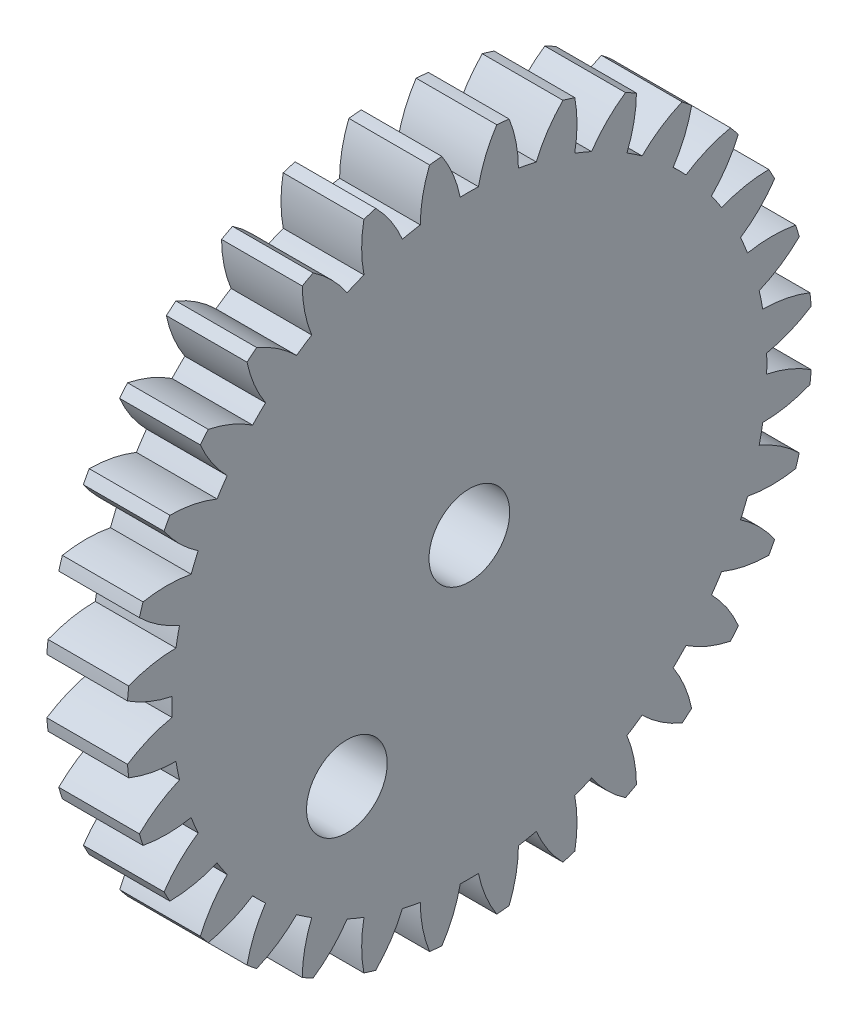
SolidWorks part; units mm, degrees
ref_plane "Plane1" through (0, 0, 0) normal (0, 0, 1) x (1, 0, 0)
ref_plane "Plane2" through (0, 0, 0) normal (0, 1, 0) x (1, 0, 0)
ref_plane "Plane3" through (0, 0, 0) normal (1, 0, 0) x (0, 0, -1)
sketch "HoldingSke" plane through (0, 0, 0) normal (0, 1, 0) x (1, 0, 0)
  line L0 (0, 0) -> (3.3922, -2.1197)
  line L1 (-15, 0) -> (100, 0) construction
  line L2 (0, 0) -> (-2.1039, 2.3779)
  line L3 (0, 0) -> (-11.863, 4.5341)
  line L4 (0, 0) -> (7.3237, 4.5764)
  line L5 (0, 0) -> (-46.8476, -17.4728)
  line L6 (0, 0) -> (-0.829, -0.5593)
  line L7 (-2.1039, 2.3779) -> (8.6586, 51.2059)
  line L8 (-76.2, 54.61) -> (-76.1, 54.61)
  line L9 (-71.009, 38.7566) -> (-53.1078, 45.2721)
  line L10 (-76.2, 71.12) -> (104.1128, 71.12)
  line L11 (0, 0) -> (-1, 0)
  line L12 (-76.2, 101.6) -> (-76.192, 101.6)
  line L13 (24.9733, 27.94) -> (52.9518, 28.4284)
  line L14 (24.9733, 27.94) -> (24.9743, 27.94)
  line L15 (24.9733, 27.94) -> (100.4006, 29.5858)
  line L16 (-63.627, -0.25) -> (-12.827, -0.25)
  circle A0 centre (0, 0) radius 0.625
  circle A1 centre (0, 0) radius 3.6865
  circle A2 centre (0, 0) radius 37.5
  circle A3 centre (0, 0) radius 0.625
  dimension "MHD" = 7.373
  dimension "Hub_dia" = 75
  dimension "Bore" = 1.25
  dimension "MBD" = 1.25
  dimension "Num_teeth" = 32
  dimension "Pitch" = 4
  dimension "Overall_len" = 50
  dimension "Show_teeth" = 32
  dimension "Thickness" = 1
  dimension "OAL" = 50.0001
  dimension "T_dim" = 0.1
  dimension "Ap" = 20
  dimension "H" = 19.05
  dimension "Pitch_radius" = 180.3128
  dimension "Width" = 1
  dimension "Backlash" = 0.008
  dimension "Addendum_fac" = 1
  dimension "Dedendum_fac" = 1.25
  dimension "Clearance_fac" = 0.25
  dimension "Dedendum_add" = 0.001
  dimension "Module" = 0.25
sketch "BasProSke" plane through (0, 0, 0) normal (0, 1, 0) x (1, 0, 0)
  line L0 (-10, 0) -> (60, 0) construction
  line L1 (0, 0) -> (0, 4.25)
  line L2 (0, 0) -> (1, 0)
  line L3 (1, 0) -> (1, 4.25)
  line L4 (1, 4.25) -> (0, 4.25)
  dimension "Thickness" = 1
  dimension "Diameter" = 8.5
revolve "Base-Revolve" add sketch "BasProSke" angle 360 about L0
sketch "TooCutSke" plane through (0, 0, 0) normal (1, 0, 0) x (0, 0, -1)
  line L1 (0, 0) -> (0, 107) construction
  line L2 (0, 0) -> (-0.2103, 3.9945) construction
  line L3 (0, 0) -> (-0.7833, 7.9532) construction
  line L4 (-0.2103, 3.9945) -> (-0.3917, 3.9766) construction
  arc A0 (0.1129, 3.6848) -> (-0.1129, 3.6848) centre (0, 0) ccw
  arc A1 (0.356, 4.2606) -> (-0.356, 4.2606) centre (0, 0) ccw
  circle A2 centre (0, 0) radius 4 construction
  circle A3 centre (0, 0) radius 3.7588 construction
  arc A4 (-0.1129, 3.6848) -> (-0.356, 4.2606) centre (-1.6801, 3.3624) ccw
  arc A5 (0.356, 4.2606) -> (0.1129, 3.6848) centre (1.6801, 3.3624) ccw
  dimension "Root_dia" = 7.373
  dimension "Overcut_dia" = 8.5508
  dimension "Pitch_dia" = 8
  dimension "Base_dia" = 7.5175
  dimension "Flank_rad" = 1.6
  dimension "Half_ang" = 5.625
  dimension "Half_CT" = 0.1823
extrude "ToothCut" cut sketch "TooCutSke" along normal through all
fillet "Breaks" [suppressed] radius 0.005
fillet "RootFillets" [suppressed] radius 0.0635
pattern_circular "TeethCuts" count 32 every 11.25 about axis through (-10, 0, 0) along (1, 0, 0) of "ToothCut", "RootFillets", "Breaks"
sketch "HubNeaOneSke" plane through (0, 0, 0) normal (-1, 0, 0) x (0, 0, 1)
  circle A0 centre (0, 0) radius 3.6865
  dimension "Diameter" = 7.373
extrude "HubNearOne" [suppressed] add sketch "HubNeaOneSke" along normal blind 49.0001
sketch "HubNeaBotSke" plane through (0, 0, 0) normal (-1, 0, 0) x (0, 0, 1)
  circle A0 centre (0, 0) radius 3.6865
  dimension "Diameter" = 7.373
extrude "HubNearBoth" [suppressed] add sketch "HubNeaBotSke" along normal blind 24.5
ref_plane "FarPln" through (1, 0, 0) normal (1, 0, 0) x (0, 0, -1)
sketch "HubFarSke" plane through (1, 0, 0) normal (1, 0, 0) x (0, 0, -1)
  circle A0 centre (0, 0) radius 3.6865
  dimension "Diameter" = 7.373
extrude "HubFar" [suppressed] add sketch "HubFarSke" along normal blind 24.5
sketch "BorSke" plane through (0, 0, 0) normal (1, 0, 0) x (0, 0, -1)
  circle A0 centre (0, 0) radius 0.5
  dimension "Diameter" = 1
extrude "Bore" cut sketch "BorSke" along normal mid plane 100.0001
sketch "KeySke" plane through (0, 0, 0) normal (1, 0, 0) x (0, 0, -1)
  line L0 (-0.05, 0) -> (-0.05, 0.725)
  line L1 (-0.05, 0.725) -> (0.05, 0.725)
  line L2 (0.05, 0.725) -> (0.05, 0)
  line L3 (0, 0) -> (0, 34) construction
  line L4 (-0.05, 0) -> (0.05, 0)
  dimension "Offset" = 0.725
extrude "Keyway" [suppressed] cut sketch "KeySke" along normal mid plane 100.0001
pattern_circular "Keyway2" [suppressed] count 2 every 90 about axis through (-10, 0, 0) along (1, 0, 0)
sketch "草圖1" plane through (1, 0, 0) normal (1, 0, 0) x (0, 0, -1)
  circle A0 centre (-1.5178, -1.9355) radius 0.5
  dimension "D1" = 1
extrude "除料-伸長1" cut sketch "草圖1" against normal blind 10
equation "' \"Module@HoldingSke\" = 6.35"
equation "' \"Num_teeth@HoldingSke\" = 12"
equation "' \"Ap@HoldingSke\" =  20"
equation "' \"Ap@HoldingSke\" = 20"
equation "' \"Width@HoldingSke\" = 0.5 * 25.4"
equation "' \"Hub_dia@HoldingSke\"= 1 * 25.4"
equation "' \"Hub_dia@HoldingSke\" = 1 * 25.4"
equation "' \"Overall_len@HoldingSke\" = 1.0 * 25.4"
equation "' \"Bore@HoldingSke\" = 0.75 * 25.4"
equation "' \"T_dim@HoldingSke\" = 0.1 * 25.4"
equation "' \"Width@KeySke\" = 0.25 * 25.4"
equation "' \"Show_teeth@HoldingSke\" = 13"
equation "' \"Backlash@HoldingSke\" = 0.009 * 25.4"
equation "' \"Addendum_fac@HoldingSke\" = 1.0"
equation "' \"Dedendum_fac@HoldingSke\" = 1.25"
equation "' \"Dedendum_add@HoldingSke\" = 0.00005 * 25.4"
equation "' \"Clearance_fac@HoldingSke\" = 0.25"
equation "\"Pitch@HoldingSke\" = 1 / \"Module@HoldingSke\""
equation "\"Overcut_dia@TooCutSke\" = (\"Num_teeth@HoldingSke\" + 2 * \"Addendum_fac@HoldingSke\") / \"Pitch@HoldingSke\" + 0.002 * 25.4"
equation "\"Pitch_dia@TooCutSke\" = \"Num_teeth@HoldingSke\" / \"Pitch@HoldingSke\""
equation "\"Base_dia@TooCutSke\" = \"Num_teeth@HoldingSke\" / \"Pitch@HoldingSke\" * cos((\"Ap@HoldingSke\"  * 3.14159265 / 180))"
equation "\"Root_dia@TooCutSke\" = (\"Num_teeth@HoldingSke\" + 2) / \"Pitch@HoldingSke\" - 2 * (\"Addendum_fac@HoldingSke\" + \"Dedendum_fac@HoldingSke\") / \"Pitch@HoldingSke\" - \"Dedendum_add@HoldingSke\" * 2"
equation "\"Half_ang@TooCutSke\" = 180 / \"Num_teeth@HoldingSke\""
equation "\"Half_CT@TooCutSke\" = \"Num_teeth@HoldingSke\" / \"Pitch@HoldingSke\" * sin((3.14159265 / 2 / \"Num_teeth@HoldingSke\")) / 2 - 7 * \"Backlash@HoldingSke\" / 4"
equation "\"Flank_rad@TooCutSke\" = \"Num_teeth@HoldingSke\" / \"Pitch@HoldingSke\" / 5"
equation "\"Radius@RootFillets\" = \"Clearance_fac@HoldingSke\" / \"Pitch@HoldingSke\" + \"Dedendum_add@HoldingSke\""
equation "\"Break_rad@Breaks\" = 0.02 / \"Pitch@HoldingSke\""
equation "\"Thickness@HoldingSke\" = \"Width@HoldingSke\""
equation "\"OAL@HoldingSke\" = \"Thickness@HoldingSke\""
equation "\"MHD@HoldingSke\" = (\"Num_teeth@HoldingSke\" + 2) / \"Pitch@HoldingSke\" - 2 * (\"Addendum_fac@HoldingSke\" + \"Dedendum_fac@HoldingSke\")  / \"Pitch@HoldingSke\" - \"Dedendum_add@HoldingSke\" * 2"
equation "\"MBD@HoldingSke\" = (\"Num_teeth@HoldingSke\" + 2) / \"Pitch@HoldingSke\" - 2 * (\"Addendum_fac@HoldingSke\" + \"Dedendum_fac@HoldingSke\")  / \"Pitch@HoldingSke\" - \"Dedendum_add@HoldingSke\" * 2 - 0.002 * 25.4"
equation "\"MHD@HoldingSke\" = ((sgn( \"MHD@HoldingSke\" - \"Hub_dia@HoldingSke\" )-1)*( \"MHD@HoldingSke\" - \"Hub_dia@HoldingSke\" ))/-2+ \"Hub_dia@HoldingSke\""
equation "\"MBD@HoldingSke\" = ((sgn( \"MBD@HoldingSke\" - \"Bore@HoldingSke\" )-1)*( \"MBD@HoldingSke\" - \"Bore@HoldingSke\" ))/-2+ \"Bore@HoldingSke\""
equation "\"OAL@HoldingSke\" = ((sgn( \"OAL@HoldingSke\" - \"Overall_len@HoldingSke\" )+1)*( \"OAL@HoldingSke\" - \"Overall_len@HoldingSke\" ))/2 + \"Overall_len@HoldingSke\" + 0.000002 * 25.4"
equation "\"Num_teeth@TeethCuts\" = int( \"Show_teeth@HoldingSke\" ) + 1"
equation "\"Num_teeth@TeethCuts\" = ((sgn( \"Num_teeth@TeethCuts\" - \"Num_teeth@HoldingSke\" )-1)*( \"Num_teeth@TeethCuts\" - \"Num_teeth@HoldingSke\" ))/-2+ \"Num_teeth@HoldingSke\""
equation "\"Num_teeth@TeethCuts\" = ((sgn( \"Num_teeth@TeethCuts\" - 2.0)+1)*( \"Num_teeth@TeethCuts\" - 2.0))/2 +2.0"
equation "\"Angle@TeethCuts\" = 360.0 / \"Num_teeth@HoldingSke\""
equation "\"Diameter@BasProSke\" = (\"Num_teeth@HoldingSke\" + 2 * \"Addendum_fac@HoldingSke\") / \"Pitch@HoldingSke\""
equation "\"Thickness@BasProSke\"  = \"Thickness@HoldingSke\""
equation "' \"Fillet_rad@BasProSke\" =  \"Thickness@HoldingSke\" * 0.05"
equation "' \"Fillet_rad@BasProSke\" = \"Thickness@HoldingSke\" * 0.05"
equation "\"MHD@HoldingSke\" = ((sgn( \"MHD@HoldingSke\" - \"Root_dia@TooCutSke\" )-1)*( \"MHD@HoldingSke\" - \"Root_dia@TooCutSke\" ))/-2+ \"Root_dia@TooCutSke\""
equation "\"Diameter@HubNeaOneSke\" = \"MHD@HoldingSke\""
equation "\"Length@HubNearOne\" = \"OAL@HoldingSke\" - \"Thickness@BasProSke\""
equation "\"Diameter@HubNeaBotSke\" = \"MHD@HoldingSke\""
equation "\"Length@HubNearBoth\" = ( \"OAL@HoldingSke\" - \"Thickness@BasProSke\" ) / 2.0"
equation "\"Thickness@FarPln\" = \"Thickness@BasProSke\""
equation "\"Diameter@HubFarSke\" = \"MHD@HoldingSke\""
equation "\"Length@HubFar\" = ( \"OAL@HoldingSke\" - \"Thickness@BasProSke\" ) / 2.0"
equation "\"D1@Bore\" = \"OAL@HoldingSke\" * 2.0"
equation "\"D1@Keyway\" = \"OAL@HoldingSke\" * 2.0"
equation "\"Offset@KeySke\" = \"T_dim@HoldingSke\" + \"MBD@HoldingSke\" / 2.0"
